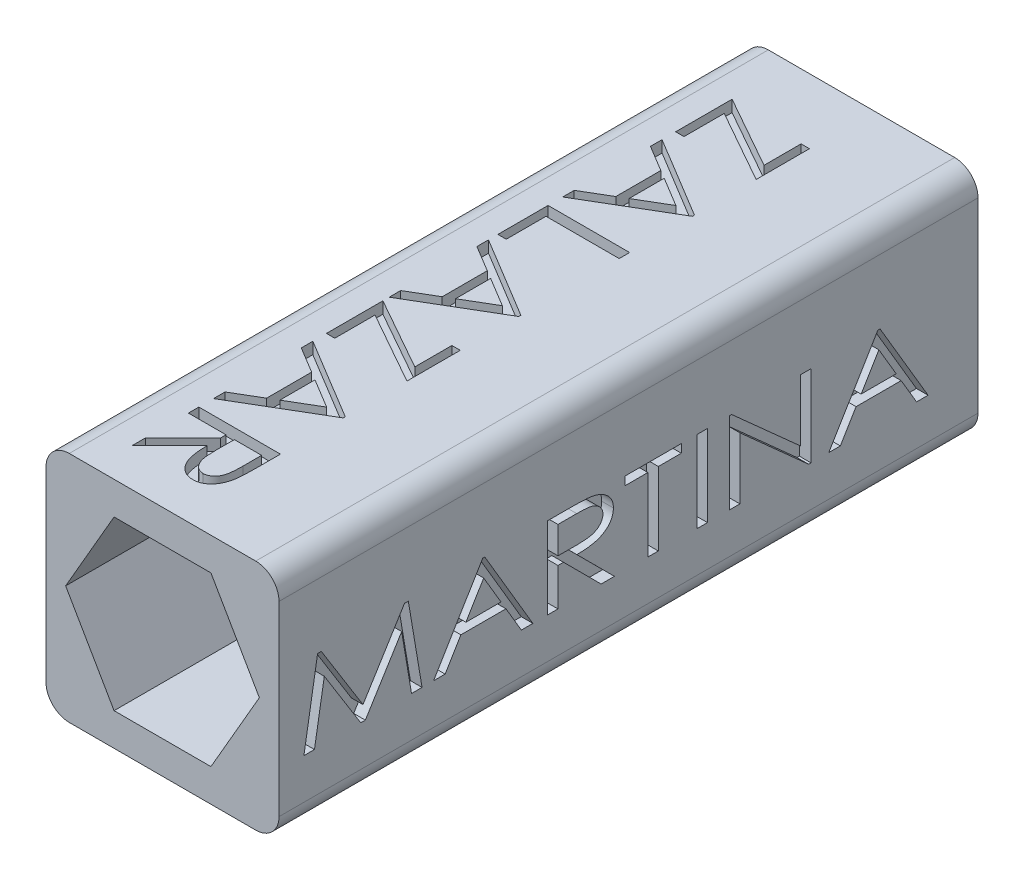
SolidWorks part; units mm, degrees
ref_plane "Alzado" through (0, 0, 0) normal (0, 0, 1) x (1, 0, 0)
ref_plane "Planta" through (0, 0, 0) normal (0, 1, 0) x (1, 0, 0)
ref_plane "Vista lateral" through (0, 0, 0) normal (1, 0, 0) x (0, 0, -1)
sketch "Croquis1" plane through (0, 0, 0) normal (1, 0, 0) x (0, 0, -1)
  line L1 (-15, -5) -> (15, -5)
  line L2 (-15, -5) -> (-15, 5)
  line L3 (-15, 5) -> (15, 5)
  line L4 (15, -5) -> (15, 5)
  line L5 (-15, -5) -> (15, 5) construction
  line L6 (-15, 5) -> (15, -5) construction
  point P0 (0, 0)
  dimension "D1" = 30
  dimension "D2" = 10
extrude "Saliente-Extruir1" add sketch "Croquis1" along normal mid plane 10
fillet "Redondeo2" radius 1 4 edges at (-5, -5, 0) (5, -5, 0) (5, 5, 0) (-5, 5, 0)
sketch "Croquis5" plane through (0, 0, 0) normal (0, 0, 1) x (1, 0, 0)
  line L1 (4.1569, 0) -> (2.0785, 3.6)
  line L2 (2.0785, 3.6) -> (-2.0785, 3.6)
  line L3 (-2.0785, 3.6) -> (-4.1569, 0)
  line L4 (-4.1569, 0) -> (-2.0785, -3.6)
  line L5 (-2.0785, -3.6) -> (2.0785, -3.6)
  line L6 (2.0785, -3.6) -> (4.1569, 0)
  circle A0 centre (0, 0) radius 3.6 construction
extrude "Cortar-Extruir3" cut sketch "Croquis5" against normal mid plane 33
sketch "Croquis6" plane through (5, 0, 0) normal (1, 0, 0) x (0, 0, -1)
  line L0 (-14.2897, -2.2654) -> (14.0407, -2.2654) construction
  text T0 "MARTINA" font "Century Gothic" height 3.5
extrude "Cortar-Extruir4" cut sketch "Croquis6" against normal blind 0.5
sketch "Croquis7" plane through (0, -5, 0) normal (0, -1, 0) x (1, 0, 0)
  line L0 (-2.5129, 13.7566) -> (-2.5129, -13.0478) construction
  text T0 "ZALAZAR" font "Century Gothic" height 3.5
extrude "Cortar-Extruir5" cut sketch "Croquis7" against normal blind 0.5
sketch "Croquis9" plane through (-5, 0, 0) normal (-1, 0, 0) x (0, 0, 1)
  line L0 (-13.1718, -2.4652) -> (13.5186, -2.4652) construction
  text T0 "MARTINA" font "Century Gothic" height 3.5
extrude "Cortar-Extruir8" cut sketch "Croquis9" against normal blind 0.5
sketch "Croquis10" plane through (0, 5, 0) normal (0, 1, 0) x (1, 0, 0)
  line L0 (-2.944, -13.7252) -> (-2.944, 13.8652) construction
  text T0 "ZALAZAR" font "Century Gothic" height 3.5
extrude "Cortar-Extruir9" cut sketch "Croquis10" against normal blind 0.5
